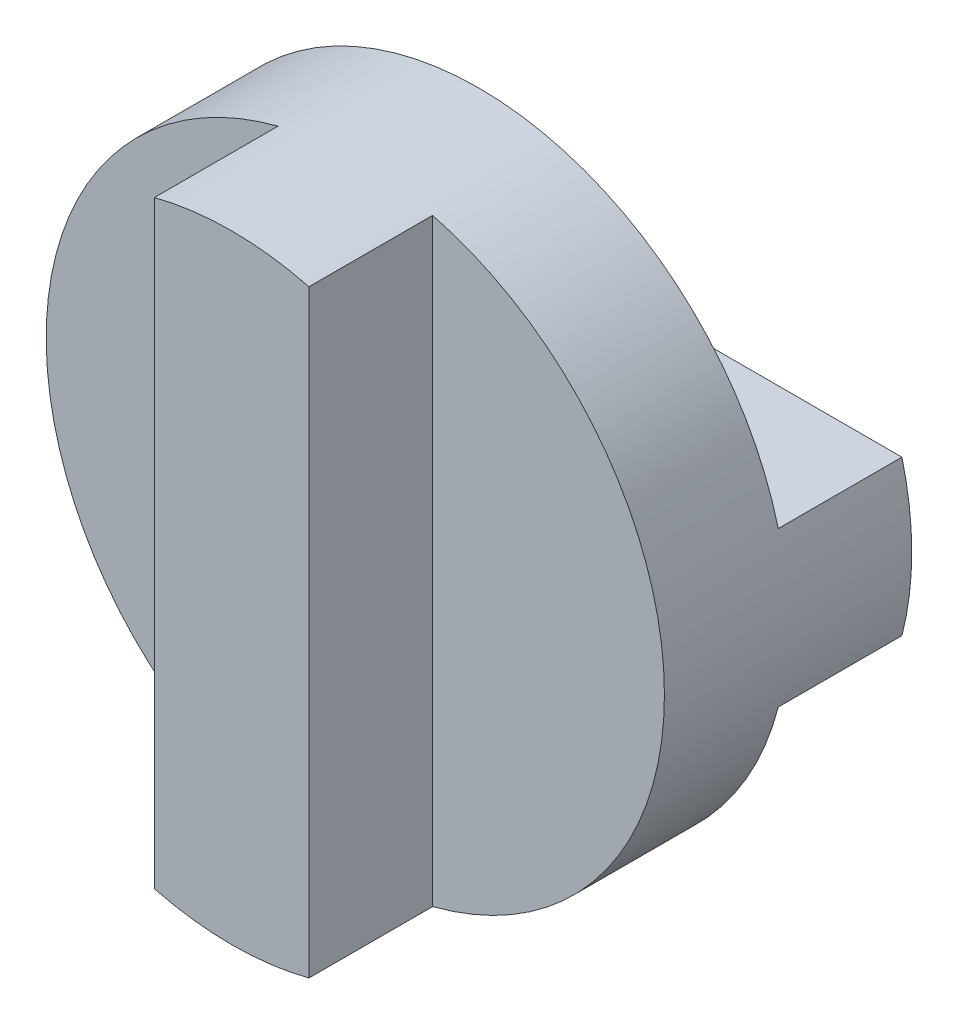
SolidWorks part; units mm, degrees
ref_plane "Front Plane" through (0, 0, 0) normal (0, 0, 1) x (1, 0, 0)
ref_plane "Top Plane" through (0, 0, 0) normal (0, 1, 0) x (1, 0, 0)
ref_plane "Right Plane" through (0, 0, 0) normal (1, 0, 0) x (0, 0, -1)
sketch "Sketch1" plane through (0, 0, 0) normal (0, 0, 1) x (1, 0, 0)
  circle A0 centre (0, 0) radius 12.7 construction
  circle A1 centre (0, 0) radius 12.7
extrude "Boss-Extrude1" add sketch "Sketch1" along normal blind 5.08
sketch "Sketch2" plane through (0, 0, 0) normal (0, 0, -1) x (-1, 0, 0)
  line L2 (12.2967, 3.175) -> (-12.2967, 3.175)
  line L3 (-12.2967, -3.175) -> (12.2967, -3.175)
  line L4 (12.2967, 3.175) -> (-12.2967, 3.175)
  line L5 (-12.2967, -3.175) -> (12.2967, -3.175)
  arc A2 (12.2967, -3.175) -> (12.2967, 3.175) centre (0, 0) ccw
  arc A3 (-12.2967, 3.175) -> (-12.2967, -3.175) centre (0, 0) ccw
  arc A4 (12.2967, -3.175) -> (12.2967, 3.175) centre (0, 0) ccw
  arc A5 (-12.2967, 3.175) -> (-12.2967, -3.175) centre (0, 0) ccw
  dimension "D1" = 0
extrude "Boss-Extrude2" add sketch "Sketch2" along normal up to surface (5.08 mm away)
sketch "Sketch4" plane through (0, 0, 5.08) normal (0, 0, 1) x (1, 0, 0)
  line L9 (-3.175, -12.2967) -> (-3.175, 12.2967)
  line L10 (3.175, 12.2967) -> (3.175, -12.2967)
  arc A1 (-3.175, 12.2967) -> (3.175, 12.2967) centre (0, 0) cw
  arc A6 (3.175, -12.2967) -> (-3.175, -12.2967) centre (0, 0) cw
extrude "Boss-Extrude3" add sketch "Sketch4" along normal blind 5.08
